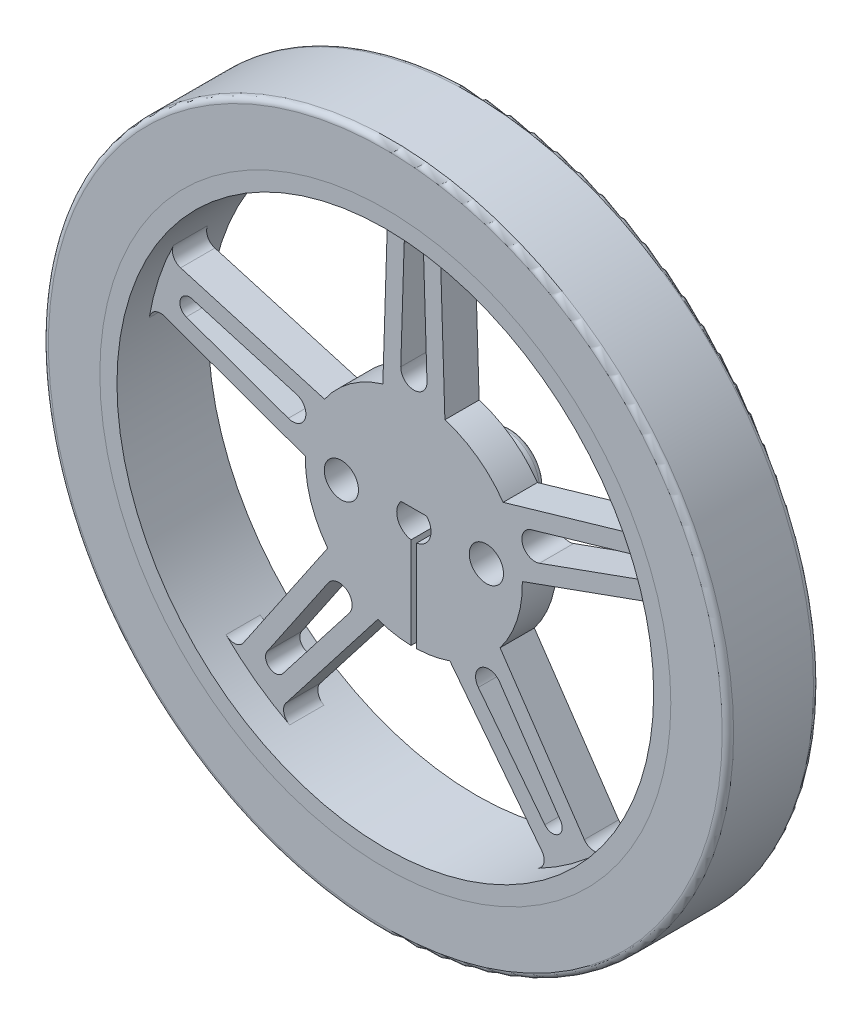
SolidWorks part; units mm, degrees
other "tire"
other "wheel"
ref_plane "Přední rovina" through (0, 0, 0) normal (0, 0, 1) x (1, 0, 0)
ref_plane "Horní rovina" through (0, 0, 0) normal (0, 1, 0) x (1, 0, 0)
ref_plane "Pravá rovina" through (0, 0, 0) normal (1, 0, 0) x (0, 0, -1)
sketch "Skica2" plane through (0, 0, 0) normal (1, 0, 0) x (0, 0, -1)
  line L0 (-1.5, 23.5) -> (-1.5, 0)
  line L1 (-2.5, 28) -> (2.5, 28)
  line L2 (2.5, 28) -> (2.5, 25)
  line L3 (2.5, 25) -> (4, 25)
  line L4 (4, 25) -> (4, 23.5)
  line L5 (4, 23.5) -> (1.5, 23.5)
  line L6 (7, 0) -> (-1.5, 0)
  line L7 (1.5, 23.5) -> (1.5, 3)
  line L8 (1.5, 3) -> (6.5, 3)
  line L9 (7, 2.5) -> (7, 0)
  line L10 (-36.9889, 0) -> (36.9889, 0) construction
  line L11 (0, 0) -> (0, 62.8313) construction
  line L13 (-4, 23.5) -> (-1.5, 23.5)
  line L14 (-4, 25) -> (-4, 23.5)
  line L15 (-2.5, 25) -> (-4, 25)
  line L16 (-2.5, 28) -> (-2.5, 25)
  arc A0 (6.5, 3) -> (7, 2.5) centre (6.5, 2.5) cw
  point P22 (0, 28)
  dimension "D9" = 0.5
  dimension "D1" = 56
  dimension "D2" = 8
  dimension "D3" = 3
  dimension "D4" = 3
  dimension "D5" = 1.5
  dimension "D6" = 6
  dimension "D7" = 11
  dimension "D8" = 1.5
revolve "Rotovat1" add sketch "Skica2" angle 360 about L10
sketch "Skica3" plane through (0, 0, 1.5) normal (0, 0, 1) x (1, 0, 0)
  line L0 (-2.3014, 22.225) -> (-2.716, 9.1035)
  line L1 (0, 0) -> (0, 29.5863) construction
  line L2 (-0.8496, 20.6768) -> (-1.1494, 11.1863)
  line L3 (2.3014, 22.225) -> (2.716, 9.1035)
  line L4 (0.8496, 20.6768) -> (1.1494, 11.1863)
  line L5 (20.426, 9.0567) -> (7.8186, 5.3962)
  line L6 (19.4023, 7.1975) -> (10.2836, 4.5499)
  line L7 (21.8484, 4.6791) -> (9.4972, 0.2301)
  line L8 (19.9274, 5.5815) -> (10.994, 2.3636)
  line L9 (14.9254, -16.6276) -> (7.5482, -5.7685)
  line L10 (12.8409, -16.2285) -> (7.5051, -8.3743)
  line L11 (11.2016, -19.3331) -> (3.1536, -8.9613)
  line L12 (11.4662, -17.2273) -> (5.6452, -9.7255)
  line L13 (-11.2016, -19.3331) -> (-3.1536, -8.9613)
  line L14 (-11.4662, -17.2273) -> (-5.6452, -9.7255)
  line L15 (-14.9254, -16.6276) -> (-7.5482, -5.7685)
  line L16 (-12.8409, -16.2285) -> (-7.5051, -8.3743)
  line L17 (-21.8484, 4.6791) -> (-9.4972, 0.2301)
  line L18 (-19.9274, 5.5815) -> (-10.994, 2.3636)
  line L19 (-20.426, 9.0567) -> (-7.8186, 5.3962)
  line L20 (-19.4023, 7.1975) -> (-10.2836, 4.5499)
  circle A0 centre (0, 0) radius 23.5 construction
  arc A1 (-0.8496, 20.6768) -> (0.8496, 20.6768) centre (0, 20.65) cw
  circle A2 centre (0, 0) radius 23.5 construction
  arc A3 (-1.1494, 11.1863) -> (1.1494, 11.1863) centre (0, 11.15) ccw
  arc A4 (-3.1536, -8.9613) -> (3.1536, -8.9613) centre (0, 0) ccw
  arc A5 (-3.4476, 23.2457) -> (-21.0426, 10.4622) centre (0, 0) ccw
  arc A6 (-2.3014, 22.225) -> (-3.4476, 23.2457) centre (-3.3009, 22.2565) ccw
  arc A7 (2.3014, 22.225) -> (3.4476, 23.2457) centre (3.3009, 22.2565) cw
  arc A8 (19.4023, 7.1975) -> (19.9274, 5.5815) centre (19.6393, 6.3812) cw
  arc A9 (10.2836, 4.5499) -> (10.994, 2.3636) centre (10.6043, 3.4455) ccw
  arc A10 (20.426, 9.0567) -> (21.0426, 10.4622) centre (20.1472, 10.017) ccw
  arc A11 (21.8484, 4.6791) -> (23.1734, 3.9044) centre (22.1873, 3.7383) cw
  arc A12 (12.8409, -16.2285) -> (11.4662, -17.2273) centre (12.1378, -16.7062) cw
  arc A13 (7.5051, -8.3743) -> (5.6452, -9.7255) centre (6.5538, -9.0205) ccw
  arc A14 (14.9254, -16.6276) -> (16.4527, -16.7797) centre (15.7526, -16.0657) ccw
  arc A15 (11.2016, -19.3331) -> (10.8743, -20.8327) centre (10.4116, -19.9462) cw
  arc A16 (-11.4662, -17.2273) -> (-12.8409, -16.2285) centre (-12.1378, -16.7062) cw
  arc A17 (-5.6452, -9.7255) -> (-7.5051, -8.3743) centre (-6.5538, -9.0205) ccw
  arc A18 (-11.2016, -19.3331) -> (-10.8743, -20.8327) centre (-10.4116, -19.9462) ccw
  arc A19 (-14.9254, -16.6276) -> (-16.4527, -16.7797) centre (-15.7526, -16.0657) cw
  arc A20 (-19.9274, 5.5815) -> (-19.4023, 7.1975) centre (-19.6393, 6.3812) cw
  arc A21 (-10.994, 2.3636) -> (-10.2836, 4.5499) centre (-10.6043, 3.4455) ccw
  arc A22 (-21.8484, 4.6791) -> (-23.1734, 3.9044) centre (-22.1873, 3.7383) ccw
  arc A23 (-20.426, 9.0567) -> (-21.0426, 10.4622) centre (-20.1472, 10.017) cw
  arc A24 (21.0426, 10.4622) -> (3.4476, 23.2457) centre (0, 0) ccw
  arc A25 (16.4527, -16.7797) -> (23.1734, 3.9044) centre (0, 0) ccw
  arc A26 (-10.8743, -20.8327) -> (10.8743, -20.8327) centre (0, 0) ccw
  arc A27 (7.5482, -5.7685) -> (9.4972, 0.2301) centre (0, 0) ccw
  arc A28 (-2.716, 9.1035) -> (-7.8186, 5.3962) centre (0, 0) ccw
  arc A29 (7.8186, 5.3962) -> (2.716, 9.1035) centre (0, 0) ccw
  arc A30 (-9.4972, 0.2301) -> (-7.5482, -5.7685) centre (0, 0) ccw
  arc A31 (-23.1734, 3.9044) -> (-16.4527, -16.7797) centre (0, 0) ccw
  point P19 (-2.2646, 23.3906)
  point P22 (2.2646, 23.3906)
  dimension "D1" = 0.85
  dimension "D2" = 1.15
  dimension "D4" = 2
  dimension "D5" = 19
  dimension "D6" = 0.5
  dimension "D7" = 1
  dimension "D8" = 1
  dimension "D3" = 1.5
  dimension "D9" = 5
extrude "Odebrat vysunutím1" cut sketch "Skica3" against normal through all
sketch "Skica4" plane through (0, 0, 1.5) normal (0, 0, 1) x (1, 0, 0)
  line L0 (-1.118, 1) -> (1.118, 1)
  line L1 (0, 0) -> (0, -11.6723) construction
  line L2 (-0.25, -1.479) -> (-0.25, -13.7188)
  line L3 (0.25, -1.479) -> (0.25, -13.7188)
  line L4 (-0.25, -13.7188) -> (0.25, -13.7188)
  arc A0 (-1.118, 1) -> (-0.25, -1.479) centre (0, 0) ccw
  arc A1 (0.25, -1.479) -> (1.118, 1) centre (0, 0) ccw
  dimension "D1" = 3
  dimension "D2" = 2.5
  dimension "D3" = 0.5
extrude "Odebrat vysunutím2" cut sketch "Skica4" against normal through all
sketch "Skica5" plane through (0, 0, 0) normal (1, 0, 0) x (0, 0, -1)
  line L0 (-4, 25) -> (-4, 29.5)
  line L1 (-3.5, 30) -> (3.5, 30)
  line L2 (4, 29.5) -> (4, 25)
  line L3 (-2.5, 25) -> (-4, 25) construction
  line L4 (-2.5, 28) -> (-2.5, -28) construction
  line L5 (2.5, 28) -> (-2.5, 28) construction
  line L6 (2.5, -28) -> (2.5, 28) construction
  line L7 (4, 25) -> (2.5, 25) construction
  line L8 (-2.5, 25) -> (-4, 25)
  line L9 (-2.5, 28) -> (-2.5, 25)
  line L10 (2.5, 28) -> (-2.5, 28)
  line L11 (2.5, 25) -> (2.5, 28)
  line L12 (4, 25) -> (2.5, 25)
  line L13 (0, 0) -> (18.2922, 0) construction
  arc A0 (3.5, 30) -> (4, 29.5) centre (3.5, 29.5) cw
  arc A1 (-4, 29.5) -> (-3.5, 30) centre (-3.5, 29.5) cw
  dimension "D2" = 0.5
  dimension "D3" = 0.5
  dimension "D1" = 60
revolve "Rotovat2" add sketch "Skica5" angle 360 about L13
sketch "Skica6" plane through (0, 0, 1.5) normal (0, 0, 1) x (1, 0, 0)
  line L0 (0, 0) -> (0, 11.3534) construction
  circle A0 centre (-6.35, 0) radius 1.5
  circle A1 centre (6.35, 0) radius 1.5
  dimension "D1" = 12.7
  dimension "D2" = 3
extrude "Odebrat vysunutím3" cut sketch "Skica6" against normal through all
